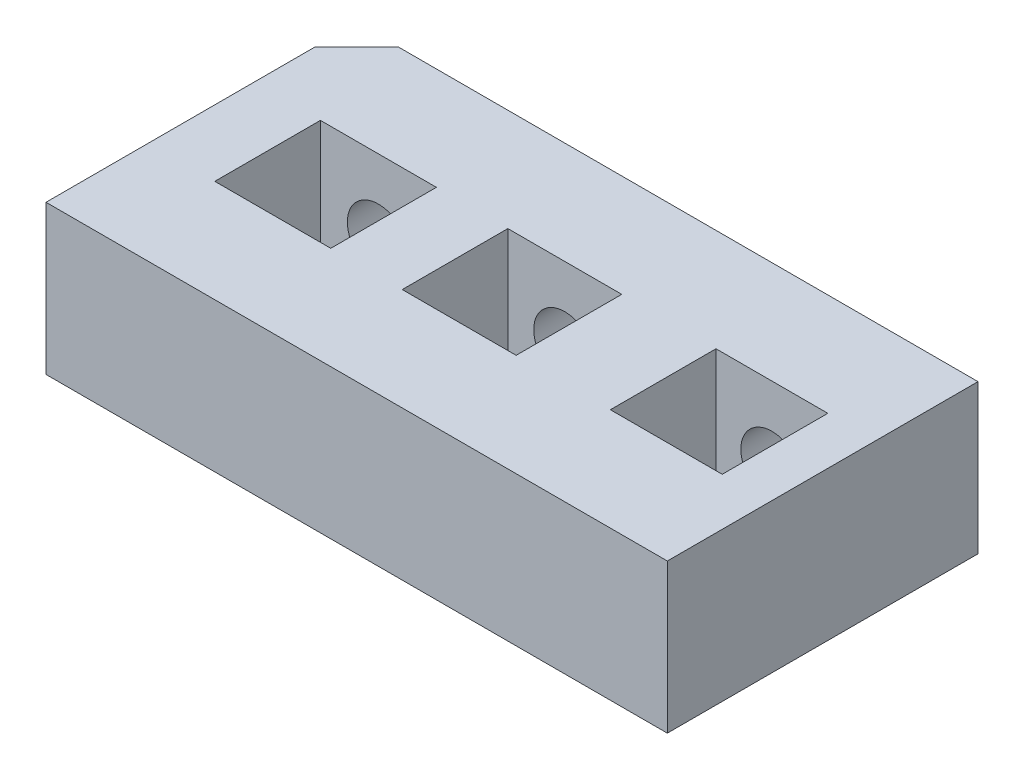
SolidWorks part; units mm, degrees
ref_plane "Front Plane" through (0, 0, 0) normal (0, 0, 1) x (1, 0, 0)
ref_plane "Top Plane" through (0, 0, 0) normal (0, 1, 0) x (1, 0, 0)
ref_plane "Right Plane" through (0, 0, 0) normal (1, 0, 0) x (0, 0, -1)
sketch "Sketch1" plane through (0, 0, 0) normal (0, 1, 0) x (1, 0, 0)
  line L1 (-15, -7.5) -> (15, -7.5)
  line L2 (-15, -7.5) -> (-15, 7.5)
  line L3 (-15, 7.5) -> (15, 7.5)
  line L4 (15, -7.5) -> (15, 7.5)
  line L5 (-15, -7.5) -> (15, 7.5) construction
  line L6 (-15, 7.5) -> (15, -7.5) construction
  point P0 (0, 0)
  dimension "D1" = 15
  dimension "D2" = 30
extrude "Boss-Extrude1" add sketch "Sketch1" along normal blind 7.2
sketch "Sketch2" plane through (0, 7.2, 0) normal (0, 1, 0) x (1, 0, 0)
  line L0 (-15, 0) -> (15, 0) construction
  line L1 (-15, 7.5) -> (-15, -7.5) construction
  line L2 (15, -7.5) -> (15, 7.5) construction
  line L4 (-11.8, -2.55) -> (-6.2, -2.55)
  line L5 (-11.8, -2.55) -> (-11.8, 2.55)
  line L6 (-11.8, 2.55) -> (-6.2, 2.55)
  line L7 (-6.2, -2.55) -> (-6.2, 2.55)
  line L8 (-11.8, -2.55) -> (-6.2, 2.55) construction
  line L9 (-11.8, 2.55) -> (-6.2, -2.55) construction
  line L10 (-2.75, -2.55) -> (2.75, -2.55)
  line L11 (-2.75, -2.55) -> (-2.75, 2.55)
  line L12 (-2.75, 2.55) -> (2.75, 2.55)
  line L13 (2.75, -2.55) -> (2.75, 2.55)
  line L14 (-2.75, -2.55) -> (2.75, 2.55) construction
  line L15 (-2.75, 2.55) -> (2.75, -2.55) construction
  line L16 (7.3, -2.55) -> (12.7, -2.55)
  line L17 (7.3, -2.55) -> (7.3, 2.55)
  line L18 (7.3, 2.55) -> (12.7, 2.55)
  line L19 (12.7, -2.55) -> (12.7, 2.55)
  line L20 (7.3, -2.55) -> (12.7, 2.55) construction
  line L21 (7.3, 2.55) -> (12.7, -2.55) construction
  point P6 (-9, 0)
  point P11 (0, 0)
  point P19 (10, 0)
  dimension "D1" = 5.1
  dimension "D2" = 5.6
  dimension "D3" = 5.5
  dimension "D4" = 5.1
  dimension "D5" = 5.1
  dimension "D6" = 5.4
  dimension "D7" = 6
  dimension "D8" = 9
  dimension "D9" = 10
extrude "Cut-Extrude1" cut sketch "Sketch2" against normal blind 7.2
sketch "Sketch4" plane through (0, 0, -7.5) normal (0, 0, -1) x (-1, 0, 0)
  line L0 (15, 3.6) -> (-15, 3.6) construction
  line L1 (15, 7.2) -> (15, 0) construction
  line L2 (-15, 7.2) -> (-15, 0) construction
  circle A0 centre (9, 3.6) radius 1.5
  circle A1 centre (0, 3.6) radius 1.5
  circle A2 centre (-10, 3.6) radius 1.5
  dimension "D1" = 3
  dimension "D2" = 6
  dimension "D3" = 9
  dimension "D4" = 10
extrude "Cut-Extrude2" cut sketch "Sketch4" against normal blind 7.2
chamfer "Chamfer1" distance 2 angle 45 1 edges at (-15, 3.6, -7.5)
